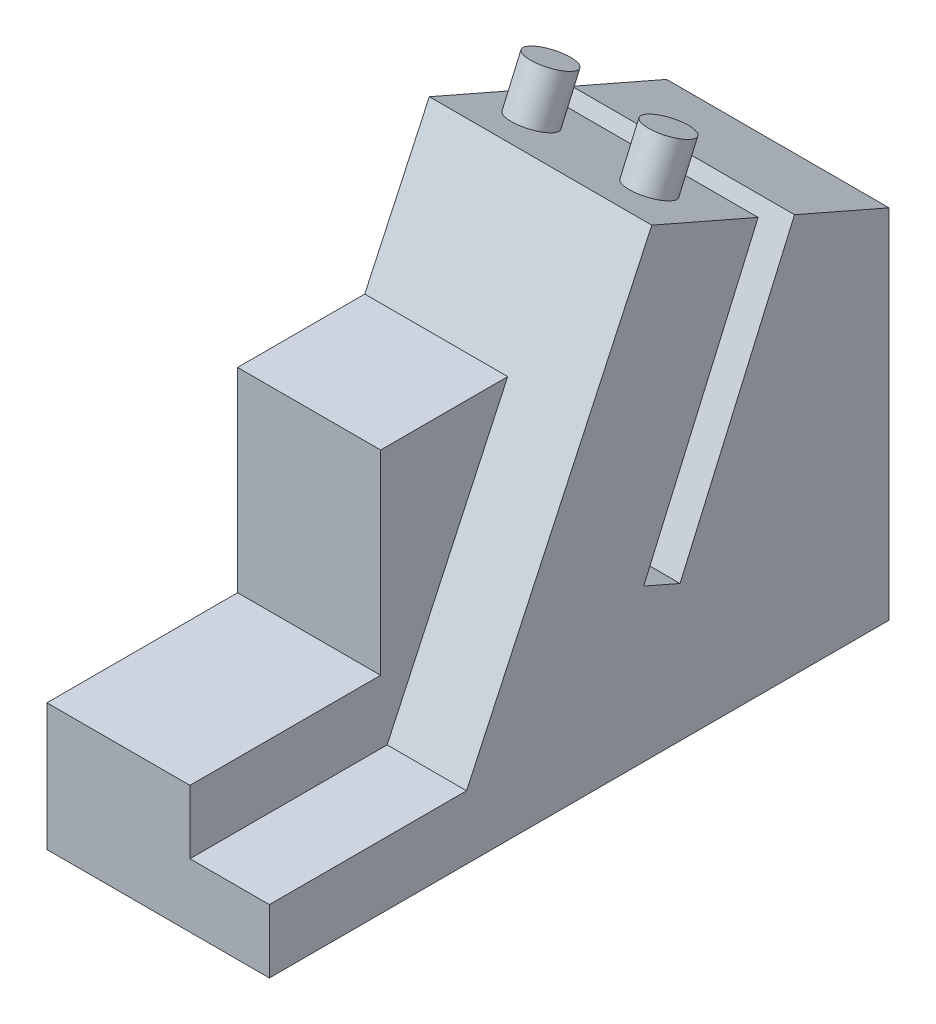
SolidWorks part; units mm, degrees
ref_plane "Front Plane" through (0, 0, 0) normal (0, 0, 1) x (1, 0, 0)
ref_plane "Top Plane" through (0, 0, 0) normal (0, 1, 0) x (1, 0, 0)
ref_plane "Right Plane" through (0, 0, 0) normal (1, 0, 0) x (0, 0, -1)
sketch "Sketch1" plane through (0, 0, 0) normal (0, 1, 0) x (1, 0, 0)
  line L1 (-14, 39) -> (14, 39)
  line L2 (-14, 39) -> (-14, -39)
  line L3 (-14, -39) -> (14, -39)
  line L4 (14, 39) -> (14, -39)
  line L5 (-14, 39) -> (14, -39) construction
  line L6 (-14, -39) -> (14, 39) construction
  point P0 (0, 0)
  dimension "D1" = 78
  dimension "D2" = 28
extrude "Boss-Extrude1" add sketch "Sketch1" along normal blind 58
sketch "Sketch2" plane through (14, 0, 0) normal (1, 0, 0) x (0, 0, -1)
  line L0 (-39, 8) -> (39, 8) construction
  line L1 (-39, 58) -> (-39, 0) construction
  line L2 (39, 58) -> (39, 0) construction
  line L3 (-39, 0) -> (39, 0) construction
  line L4 (-39, 8) -> (-14.1818, 8)
  line L5 (-14.1818, 8) -> (9.1335, 58)
  line L6 (-39, 58) -> (39, 58) construction
  line L9 (-39, 8) -> (-39, 58)
  line L10 (-39, 58) -> (9.1335, 58)
  dimension "D1" = 8
  dimension "D2" = 65
extrude "Cut-Extrude1" cut sketch "Sketch2" against normal blind 10 contours L5 L4 L9 L10
sketch "Sketch3" plane through (4, 0, 0) normal (1, 0, 0) x (0, 0, -1)
  line L0 (-39, 8) -> (-39, 16) construction
  line L1 (-39, 8) -> (-39, 58) construction
  line L2 (-39, 16) -> (-15, 16) construction
  line L3 (-15, 16) -> (-15, 40.5575) construction
  line L4 (-15, 40.5575) -> (1, 40.5575) construction
  line L5 (-14.1818, 8) -> (9.1335, 58) construction
  line L6 (-39, 16) -> (-15, 16)
  line L7 (-15, 16) -> (-15, 40.5575)
  line L8 (-15, 40.5575) -> (1, 40.5575)
  line L9 (1, 40.5575) -> (9.1335, 58)
  line L10 (9.1335, 58) -> (-39, 58)
  line L11 (-39, 58) -> (-39, 16)
  dimension "D1" = 8
  dimension "D2" = 24
  dimension "D3" = 16
extrude "Cut-Extrude2" cut sketch "Sketch3" against normal blind 20
sketch "Sketch4" plane through (14, 0, 0) normal (1, 0, 0) x (0, 0, -1)
  line L0 (9.1335, 58) -> (22.5177, 52.1545)
  line L1 (39, 58) -> (39, 0) construction
  line L2 (22.5177, 52.1545) -> (8.1091, 19.1637)
  line L3 (8.1091, 19.1637) -> (12.6912, 17.1626)
  line L4 (12.6912, 17.1626) -> (27.0997, 50.1534)
  line L5 (27.0997, 50.1534) -> (39, 44.956)
  line L6 (9.1335, 58) -> (39, 58)
  line L7 (39, 58) -> (39, 44.956)
  dimension "D1" = 5
  dimension "D2" = 36
extrude "Cut-Extrude3" cut sketch "Sketch4" against normal blind 30
sketch "Sketch5" plane through (0, 52.059, -22.7365) normal (0, 0.9164, -0.4002) x (1, 0, 0)
  line L0 (-14, -7.3437) -> (14, -7.3437) construction
  line L4 (-14, -14.8437) -> (-14, -0.2388) construction
  line L5 (14, -14.8437) -> (14, -0.2388) construction
  line L6 (-14, -14.8437) -> (14, -14.8437) construction
  line L7 (-14, -0.2388) -> (14, -0.2388) construction
  circle A1 centre (-8.021, -7.3437) radius 2.75
  circle A2 centre (6.8184, -7.3437) radius 2.75
  dimension "D3" = 5.5
  dimension "D4" = 5.5
  dimension "D1" = 7.5
  dimension "D2" = 14.6049
extrude "Boss-Extrude2" add sketch "Sketch5" along normal blind 6
